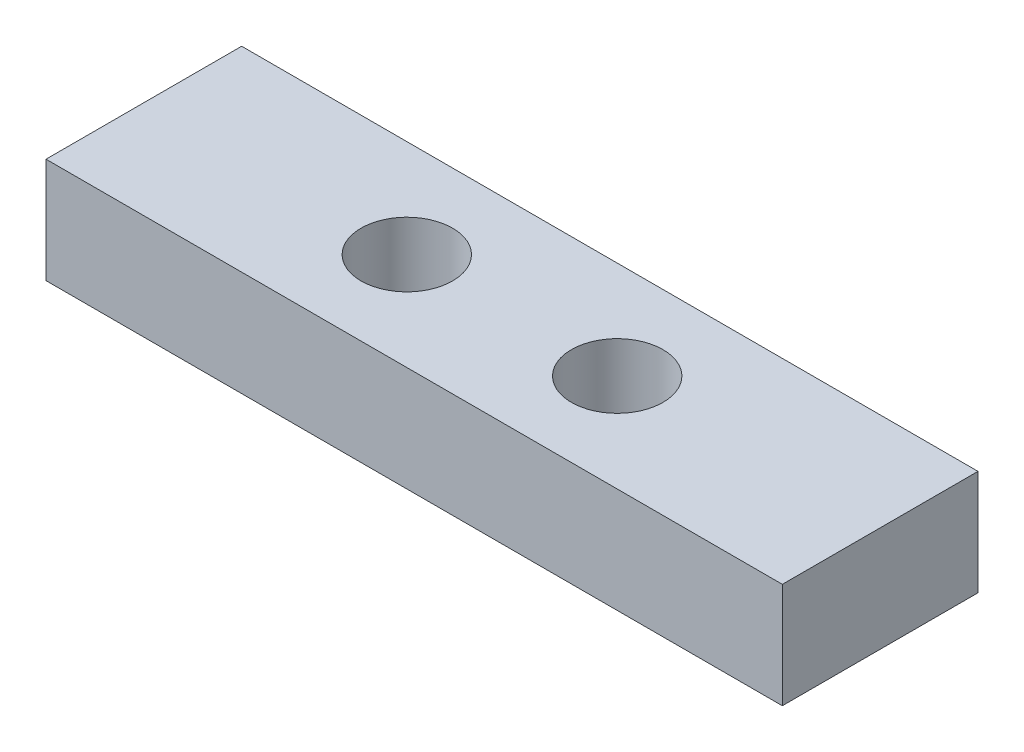
SolidWorks part; units mm, degrees
ref_plane "前视基准面" through (0, 0, 0) normal (0, 0, 1) x (1, 0, 0)
ref_plane "上视基准面" through (0, 0, 0) normal (0, 1, 0) x (1, 0, 0)
ref_plane "右视基准面" through (0, 0, 0) normal (1, 0, 0) x (0, 0, -1)
sketch "草图1" plane through (0, 0, 0) normal (0, 1, 0) x (1, 0, 0)
  line L0 (0, -55) -> (0, 55) construction
  line L2 (-17.5, -4.65) -> (17.5, -4.65)
  line L3 (-17.5, -4.65) -> (-17.5, 4.65)
  line L4 (-17.5, 4.65) -> (17.5, 4.65)
  line L5 (17.5, -4.65) -> (17.5, 4.65)
  line L6 (-17.5, -4.65) -> (17.5, 4.65) construction
  line L7 (-17.5, 4.65) -> (17.5, -4.65) construction
  circle A0 centre (-5, 0) radius 2.175
  circle A1 centre (5, 0) radius 2.175
  point P6 (0, 0)
  dimension "D1" = 10
  dimension "D2" = 4.35
  dimension "D3" = 9.3
  dimension "D4" = 35
extrude "凸台-拉伸1" add sketch "草图1" along normal blind 5
